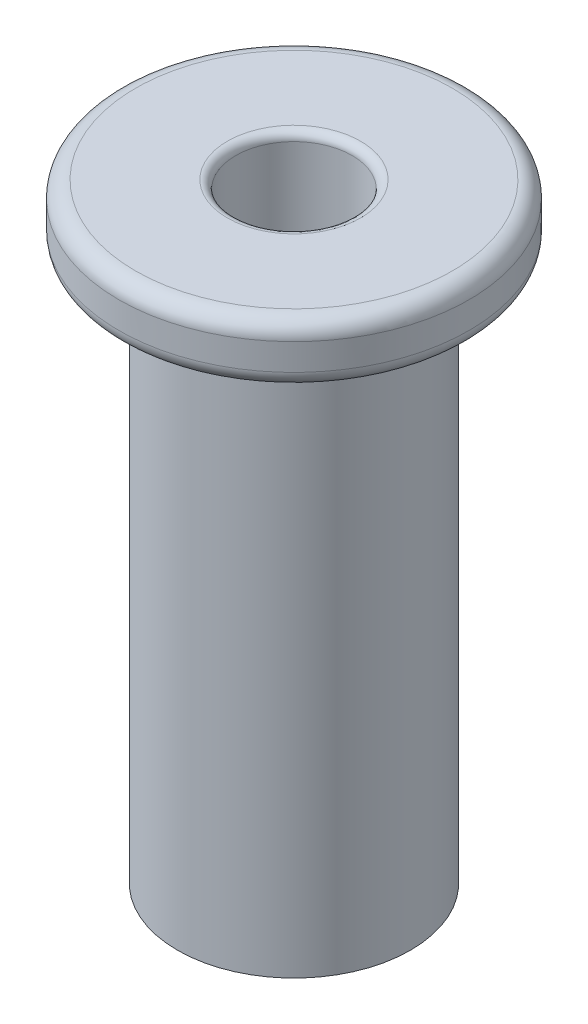
SolidWorks part; units mm, degrees
material "Ti-6Al-4VSolution treated and aged (SS)"
ref_plane "Front" through (0, 0, 0) normal (0, 0, 1) x (1, 0, 0)
ref_plane "Top" through (0, 0, 0) normal (0, 1, 0) x (1, 0, 0)
ref_plane "Right" through (0, 0, 0) normal (1, 0, 0) x (0, 0, -1)
sketch "Sketch1" plane through (0, 0, 0) normal (0, 1, 0) x (1, 0, 0)
  circle A0 centre (0, 0) radius 5.2575
  dimension "D1" = 10.515
extrude "Boss-Extrude2" add sketch "Sketch1" along normal blind 18.3
ref_plane "Plane1" through (0, 0, 0) normal (0, -1, 0) x (-1, 0, 0)
sketch "Sketch3" plane through (0, 0, 0) normal (0, -1, 0) x (-1, 0, 0)
  circle A0 centre (0, 0) radius 1.75
  dimension "D1" = 3.5
extrude "Cut-Extrude2" cut sketch "Sketch3" against normal blind 19.8
sketch "Sketch4" plane through (0, 0, 0) normal (0, -1, 0) x (-1, 0, 0)
  circle A0 centre (0, 0) radius 3.5
  circle A1 centre (0, 0) radius 5.2575
  circle A2 centre (0, 0) radius 5.2575 construction
  dimension "D1" = 7
extrude "Cut-Extrude3" cut sketch "Sketch4" against normal blind 16.5
fillet "Fillet1" radius 0.5 1 edges at (0, 18.3, 5.2575)
fillet "Fillet2" radius 0.25 1 edges at (0, 18.3, 1.75)
fillet "Fillet3" radius 0.5 1 edges at (0, 16.5, -5.2575)
